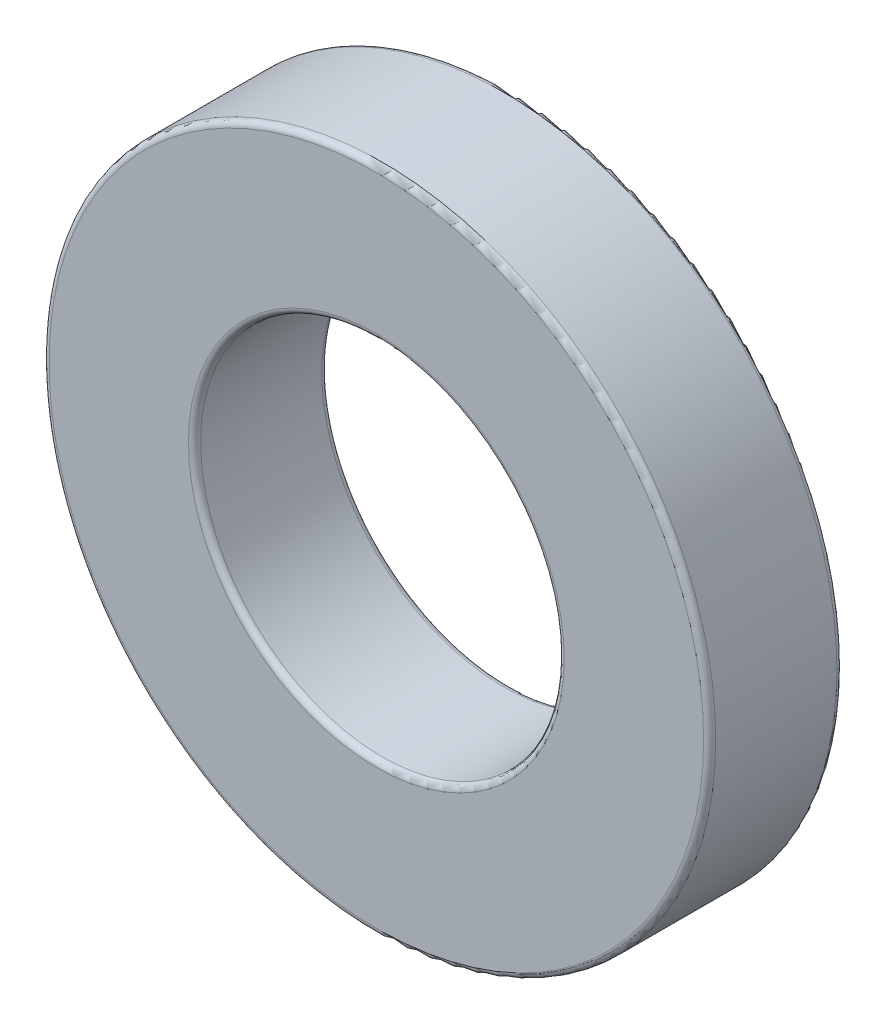
SolidWorks part; units mm, degrees
ref_plane "Front" through (0, 0, 0) normal (0, 0, 1) x (1, 0, 0)
ref_plane "Top" through (0, 0, 0) normal (0, 1, 0) x (1, 0, 0)
ref_plane "Right" through (0, 0, 0) normal (1, 0, 0) x (0, 0, -1)
sketch "Çizim1" plane through (0, 0, 0) normal (0, 0, 1) x (1, 0, 0)
  circle A0 centre (0, 0) radius 30
  circle A1 centre (0, 0) radius 55
  dimension "D1" = 110
  dimension "D2" = 60
extrude "Yükseklik-Ekstrüzyon1" add sketch "Çizim1" along normal blind 22
fillet "Radyus1" radius 1 4 edges at (55, 0, 0) (30, 0, 0) (30, 0, 22) (55, 0, 22)
